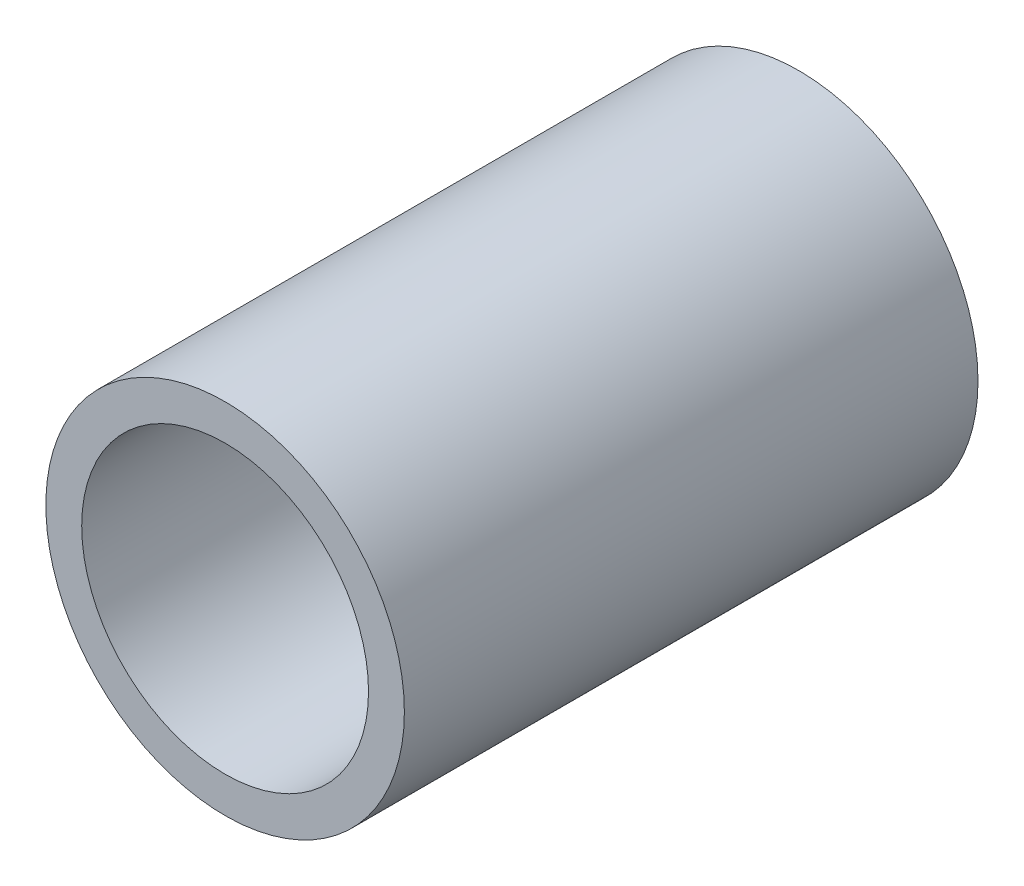
SolidWorks part; units mm, degrees
ref_plane "Front Plane" through (0, 0, 0) normal (0, 0, 1) x (1, 0, 0)
ref_plane "Top Plane" through (0, 0, 0) normal (0, 1, 0) x (1, 0, 0)
ref_plane "Right Plane" through (0, 0, 0) normal (1, 0, 0) x (0, 0, -1)
sketch "Sketch1" plane through (0, 0, 0) normal (0, 0, 1) x (1, 0, 0)
  circle A0 centre (0, 0) radius 3.9688
  dimension "D1" = 7.9375
extrude "Boss-Extrude1" add sketch "Sketch1" along normal blind 12.7
sketch "Sketch2" plane through (0, 0, 12.7) normal (0, 0, 1) x (1, 0, 0)
  circle A0 centre (0, 0) radius 3.175
  dimension "D1" = 6.35
extrude "Cut-Extrude1" cut sketch "Sketch2" against normal through all
